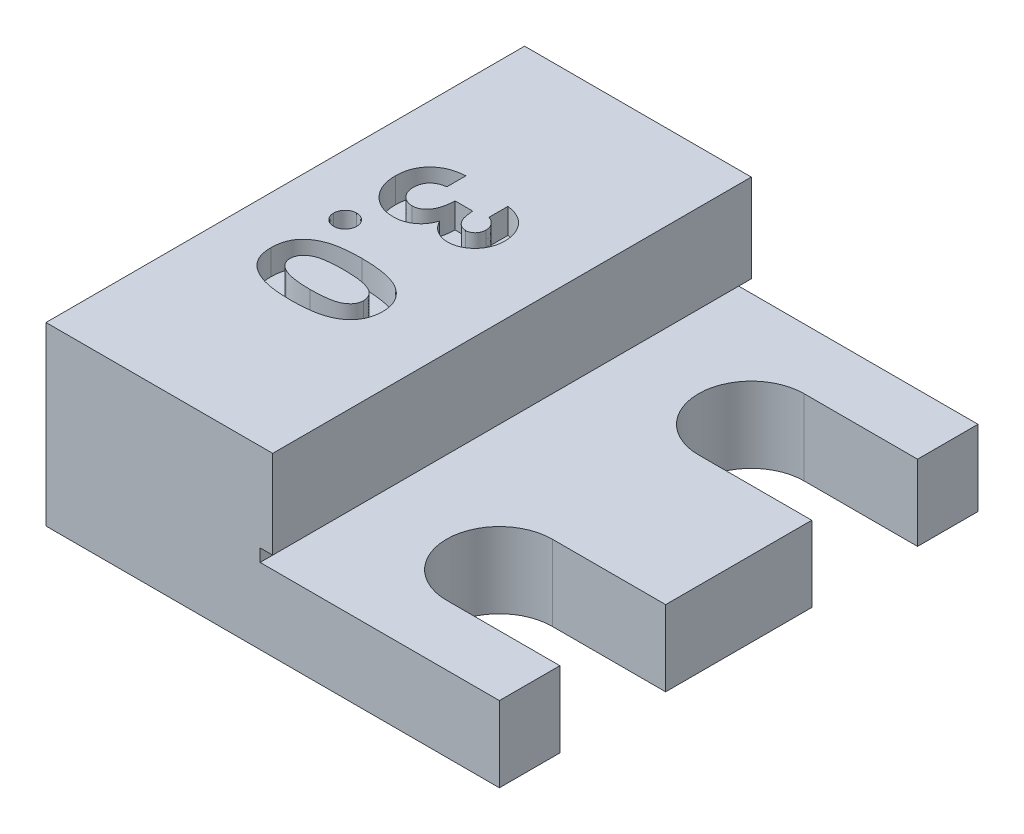
SolidWorks part; units mm, degrees
ref_plane "Front Plane" through (0, 0, 0) normal (0, 0, 1) x (1, 0, 0)
ref_plane "Top Plane" through (0, 0, 0) normal (0, 1, 0) x (1, 0, 0)
ref_plane "Right Plane" through (0, 0, 0) normal (1, 0, 0) x (0, 0, -1)
sketch "Sketch1" plane through (0, 0, 0) normal (0, 0, 1) x (1, 0, 0)
  line L1 (0, 0) -> (18, 0)
  line L2 (0, 0) -> (0, 7)
  line L7 (18, 3) -> (9, 3)
  line L8 (9, 3.5) -> (9, 7)
  line L9 (9, 7) -> (0, 7)
  line L10 (18, 3) -> (18, 0)
  line L11 (9, 3) -> (8.5, 3)
  line L12 (8.5, 3) -> (8.5, 3.5)
  line L13 (8.5, 3.5) -> (9, 3.5)
  point P10 (8.8196, 3.5)
  dimension "D1" = 18
  dimension "D2" = 3
  dimension "D3" = 9
  dimension "D4" = 0.5
  dimension "D5" = 0.5
  dimension "D6" = 7
extrude "Boss-Extrude1" add sketch "Sketch1" along normal blind 19
sketch "Sketch2" plane through (0, 7, 0) normal (0, 1, 0) x (1, 0, 0)
  line L0 (18, -9.5) -> (0, -9.5) construction
  line L2 (0, -19) -> (0, 0) construction
  line L3 (13.5, -4.5) -> (13.5, -14.5) construction
  line L4 (13.5, -2.4) -> (18, -2.4)
  line L5 (13.5, -6.6) -> (18, -6.6)
  line L6 (18, -6.6) -> (18, -2.4)
  line L7 (13.5, -12.4) -> (18, -12.4)
  line L8 (18, -12.4) -> (18, -16.6)
  line L9 (18, -16.6) -> (13.5, -16.6)
  line L10 (9, -19) -> (9, 0) construction
  line L11 (18, -19) -> (18, 0) construction
  arc A0 (13.5, -2.4) -> (13.5, -6.6) centre (13.5, -4.5) ccw
  arc A1 (13.5, -12.4) -> (13.5, -16.6) centre (13.5, -14.5) ccw
  point P2 (16, -12.9)
  point P3 (16, -17.1)
  point P8 (13.5, -9.5)
  point P19 (25, -7.1)
  point P20 (16, -10)
  point P23 (25, -7.1)
  point P24 (16, -7.1)
  dimension "D2" = 4.2
  dimension "D1" = 10
  dimension "D3" = 4.5
extrude "Cut-Extrude1" cut sketch "Sketch2" against normal through all
sketch "Sketch3" plane through (0, 7, 0) normal (0, 1, 0) x (1, 0, 0)
  line L0 (2, 0) -> (2, -19) construction
  line L1 (9, 0) -> (0, 0) construction
  line L2 (9, -19) -> (0, -19) construction
  line L3 (0, -19) -> (0, 0) construction
  text T0 "3.0" font "Century Gothic" height 4.2
  dimension "D1" = 2
extrude "Cut-Extrude2" cut sketch "Sketch3" against normal blind 1
sketch "Sketch4" plane through (0, 0, 0) normal (0, -1, 0) x (1, 0, 0)
  line L0 (9, 19) -> (9, 0) construction
  line L1 (9, 19) -> (9, 0)
  line L3 (9, 9.5) -> (0, 9.5) construction
  line L4 (0, 19) -> (0, 0) construction
  line L5 (0, 19) -> (18, 19) construction
  line L6 (7.5, 1.5) -> (1.5, 1.5)
  line L7 (7.5, 1.5) -> (7.5, 17.5)
  line L8 (7.5, 17.5) -> (1.5, 17.5)
  line L9 (1.5, 1.5) -> (1.5, 17.5)
  line L10 (7.5, 1.5) -> (1.5, 17.5) construction
  line L11 (7.5, 17.5) -> (1.5, 1.5) construction
  point P6 (4.5, 9.5)
  dimension "D1" = 1.5
  dimension "D2" = 1.5
extrude "Cut-Extrude3" cut sketch "Sketch4" against normal offset from surface (5 mm away) 1 contours L9 L6 L7 L8 up to face at (3.8567, 6, 12.0456)
